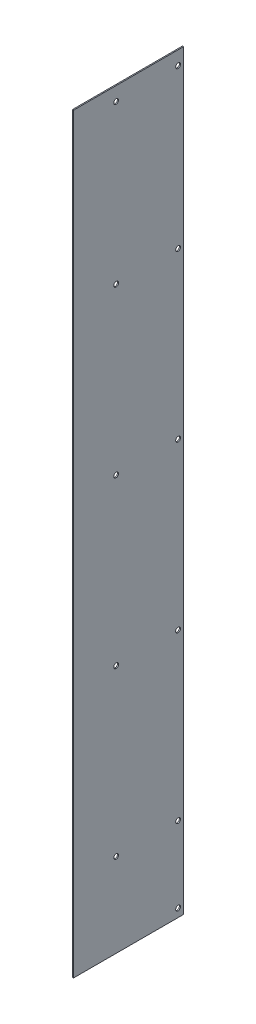
SolidWorks part; units mm, degrees
ref_plane "Front" through (0, 0, 0) normal (0, 0, 1) x (1, 0, 0)
ref_plane "Top" through (0, 0, 0) normal (0, 1, 0) x (1, 0, 0)
ref_plane "Right" through (0, 0, 0) normal (1, 0, 0) x (0, 0, -1)
sketch "Sketch1" plane through (0, 0, 0) normal (1, 0, 0) x (0, 0, -1)
  line L1 (160, 0) -> (160, 1092)
  line L2 (160, 0) -> (0, 0)
  line L3 (0, 0) -> (0, 1092)
  line L4 (160, 1092) -> (0, 1092)
  dimension "D1" = 160
  dimension "D2" = 1092
extrude "Boss-Extrude1" add sketch "Sketch1" along normal blind 1.6
hole_wizard "Ø7.0 (7) Diameter Hole1" positions "Sketch3" profile "Sketch2" hole size "Ø7.0" standard "JIS"
sketch "Sketch3" plane through (0, 0, 0) normal (-1, 0, 0) x (0, 0, 1)
  line L5 (0, 0) -> (-160, 0) construction
  line L7 (0, 1092) -> (0, 0) construction
  point P0 (-152, 12)
  point P29 (-152, 1072)
  point P31 (-62, 1072)
  dimension "D1" = 90
  dimension "D2" = 12
  dimension "D3" = 62
  dimension "D4" = 1060
sketch "Sketch2" plane through (0, 12, -152) normal (0, 1, 0) x (0, 0, 1)
  line L0 (0, 0) -> (0, 14.103)
  line L1 (0, 14.103) -> (3.5, 12)
  line L2 (3.5, 12) -> (3.5, 0)
  line L5 (3.5, 0) -> (0, 0)
  line L10 (0, 14.103) -> (-3.5, 12) construction
  line L11 (0, -6.35) -> (0, 107.95) construction
  dimension "Hole Dia." = 7
  dimension "Hole Depth" = 12
  dimension "Drill Angle" = 118
hole_wizard "Ø7.0 (7) Diameter Hole3" positions "Sketch5" profile "Sketch4" hole size "Ø7.0" standard "JIS"
sketch "Sketch5" plane through (0, 0, 0) normal (-1, 0, 0) x (0, 0, 1)
  circle A1 centre (-152, 12) radius 3.5 construction
  point P13 (-152, 122)
  point P15 (-62, 122)
  dimension "D1" = 110
  dimension "D2" = 90
sketch "Sketch4" plane through (0, 122, -152) normal (0, 1, 0) x (0, 0, 1)
  line L0 (0, 0) -> (0, 14.103)
  line L1 (0, 14.103) -> (3.5, 12)
  line L2 (3.5, 12) -> (3.5, 0)
  line L5 (3.5, 0) -> (0, 0)
  line L10 (0, 14.103) -> (-3.5, 12) construction
  line L11 (0, -6.35) -> (0, 107.95) construction
  dimension "Hole Dia." = 7
  dimension "Hole Depth" = 12
  dimension "Drill Angle" = 118
pattern_linear "LPattern1" count 4 spacing 240 along (0, 1, 0) of "Ø7.0 (7) Diameter Hole3"
